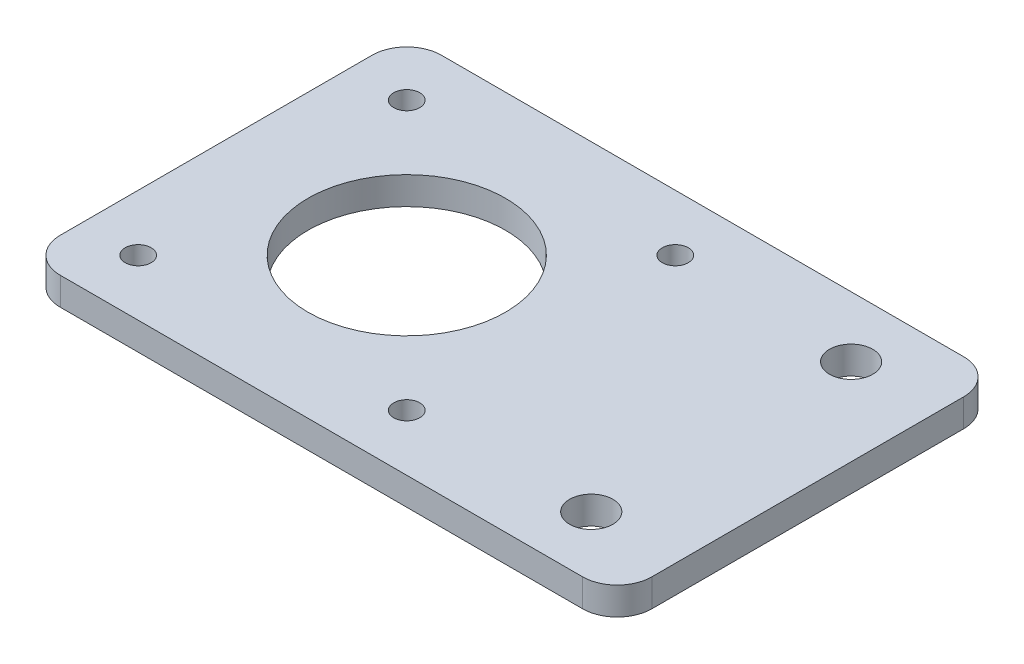
SolidWorks part; units mm, degrees
ref_plane "Front Plane" through (0, 0, 0) normal (0, 0, 1) x (1, 0, 0)
ref_plane "Top Plane" through (0, 0, 0) normal (0, 1, 0) x (1, 0, 0)
ref_plane "Right Plane" through (0, 0, 0) normal (1, 0, 0) x (0, 0, -1)
sketch "Sketch1" plane through (0, 0, 0) normal (0, 1, 0) x (1, 0, 0)
  line L1 (-34.15, 22) -> (34.15, 22)
  line L2 (-34.15, 22) -> (-34.15, -22)
  line L3 (-34.15, -22) -> (34.15, -22)
  line L4 (34.15, 22) -> (34.15, -22)
  line L5 (-34.15, 22) -> (34.15, -22) construction
  line L6 (-34.15, -22) -> (34.15, 22) construction
  point P0 (0, 0)
  dimension "D1" = 44
  dimension "D2" = 68.3
extrude "Boss-Extrude1" add sketch "Sketch1" along normal blind 3.2
sketch "Sketch2" plane through (0, 3.2, 0) normal (0, 1, 0) x (1, 0, 0)
  line L0 (-34.15, 0) -> (34.15, 0) construction
  line L1 (-34.15, 22) -> (-34.15, -22) construction
  line L2 (34.15, -22) -> (34.15, 22) construction
  line L3 (24.15, -15) -> (24.15, 15) construction
  line L5 (-27.65, 15.5) -> (3.35, 15.5) construction
  line L6 (-27.65, 15.5) -> (-27.65, -15.5) construction
  line L7 (-27.65, -15.5) -> (3.35, -15.5) construction
  line L8 (3.35, 15.5) -> (3.35, -15.5) construction
  line L9 (-27.65, 15.5) -> (3.35, -15.5) construction
  line L10 (-27.65, -15.5) -> (3.35, 15.5) construction
  circle A0 centre (-12.15, 0) radius 11.4
  circle A1 centre (24.15, 15) radius 2.5
  circle A2 centre (24.15, -15) radius 2.5
  circle A3 centre (-27.65, 15.5) radius 1.5
  circle A4 centre (3.35, 15.5) radius 1.5
  circle A5 centre (3.35, -15.5) radius 1.5
  circle A6 centre (-27.65, -15.5) radius 1.5
  point P11 (24.15, 0)
  dimension "D1" = 22.8
  dimension "D3" = 5
  dimension "D7" = 3
  dimension "D2" = 22
  dimension "D4" = 30
  dimension "D5" = 10
  dimension "D6" = 31
extrude "Cut-Extrude2" cut sketch "Sketch2" against normal through all
fillet "Fillet1" radius 4 4 edges at (34.15, 1.6, 22) (-34.15, 1.6, 22) (-34.15, 1.6, -22) (34.15, 1.6, -22)
